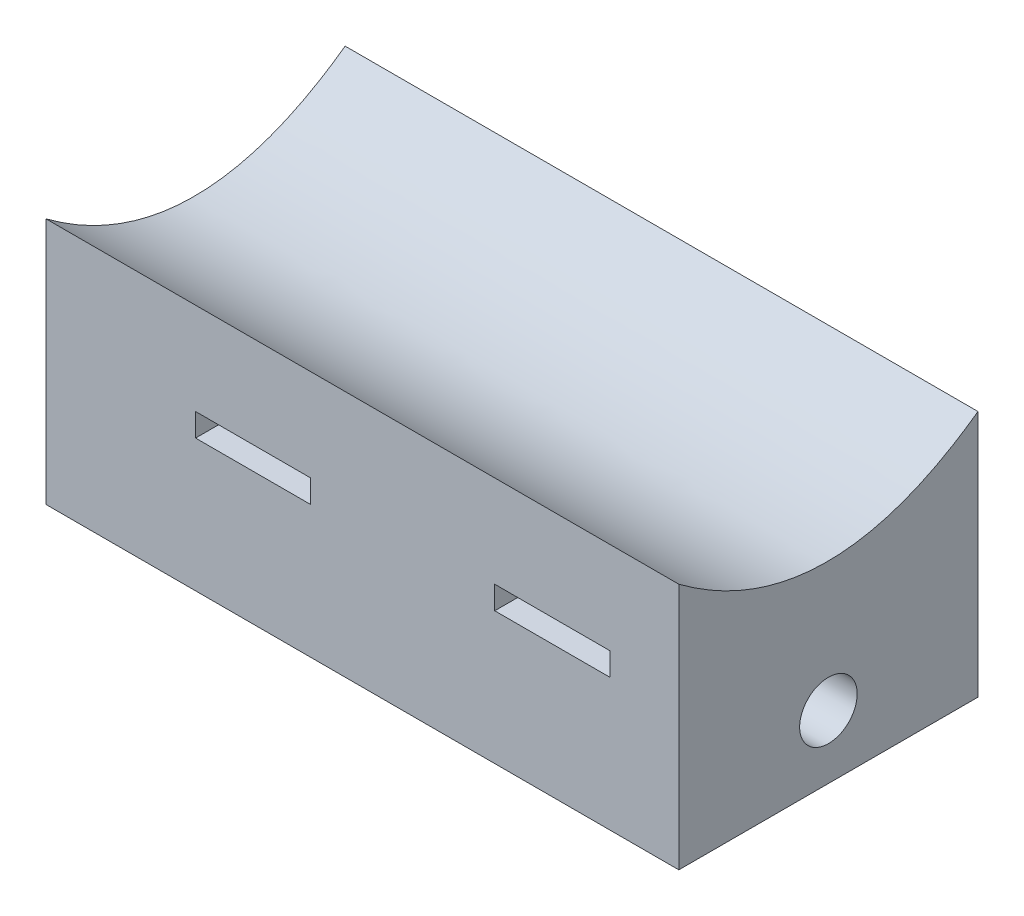
SolidWorks part; units mm, degrees
ref_plane "Plan de face" through (0, 0, 0) normal (0, 0, 1) x (1, 0, 0)
ref_plane "Plan de dessus" through (0, 0, 0) normal (0, 1, 0) x (1, 0, 0)
ref_plane "Plan de droite" through (0, 0, 0) normal (1, 0, 0) x (0, 0, -1)
sketch "Esquisse1" plane through (0, 0, 0) normal (0, 1, 0) x (1, 0, 0)
  line L1 (-24.8567, 8.6488) -> (30.1433, 8.6488)
  line L2 (-24.8567, 8.6488) -> (-24.8567, -17.3512)
  line L3 (-24.8567, -17.3512) -> (30.1433, -17.3512)
  line L4 (30.1433, 8.6488) -> (30.1433, -17.3512)
  dimension "D1" = 55
  dimension "D2" = 26
extrude "Boss.-Extru.1" add sketch "Esquisse1" along normal blind 25
sketch "Esquisse2" plane through (0, 0, 17.3512) normal (0, 0, 1) x (1, 0, 0)
  line L1 (30.1433, 25) -> (30.1433, 0) construction
  line L2 (14.1433, 17) -> (24.1433, 17)
  line L3 (14.1433, 17) -> (14.1433, 15)
  line L4 (14.1433, 15) -> (24.1433, 15)
  line L5 (24.1433, 17) -> (24.1433, 15)
  line L6 (-24.8567, 25) -> (30.1433, 25) construction
  line L7 (6.1433, 25) -> (6.1433, 0) construction
  line L8 (-24.8567, 0) -> (30.1433, 0) construction
  line L9 (-1.8567, 17) -> (-1.8567, 15)
  line L10 (-1.8567, 15) -> (-11.8567, 15)
  line L11 (-11.8567, 17) -> (-11.8567, 15)
  line L12 (-1.8567, 17) -> (-11.8567, 17)
  dimension "D1" = 10
  dimension "D2" = 2
  dimension "D3" = 6
  dimension "D4" = 8
  dimension "D5" = 24
extrude "Enlèv. mat.-Extru.1" cut sketch "Esquisse2" against normal up to next
sketch "Esquisse5" plane through (30.1433, 0, 0) normal (1, 0, 0) x (0, 0, -1)
  line L0 (8.6488, 25) -> (8.6488, 0) construction
  line L1 (-17.3512, 25) -> (8.6488, 25) construction
  line L2 (-17.3512, 25) -> (8.6488, 25)
  line L3 (-4.3512, 25) -> (-4.3512, 3.5) construction
  line L4 (-17.3512, 0) -> (8.6488, 0)
  line L5 (-17.3512, 0) -> (-17.3512, 3.5)
  line L6 (-17.3512, 3.5) -> (8.6488, 3.5)
  line L7 (8.6488, 0) -> (8.6488, 3.5)
  circle A0 centre (-4.3512, 9) radius 2.5
  spline S0 degree 2 poles (-17.3512, 25) (-4.5869, 15.5026) (8.6488, 25) knots 0 0 0 1 1 1
  point P18 (-4.3512, 9)
  dimension "D2" = 16
  dimension "D3" = 3.5
extrude "Enlèv. mat.-Extru.5" cut sketch "Esquisse5" against normal up to next
sketch "Esquisse9" plane through (0, 0, -8.6488) normal (0, 0, -1) x (-1, 0, 0)
  line L0 (-24.1433, 17) -> (-30.1433, 17) construction
  line L1 (-30.1433, 25) -> (-30.1433, 3.5) construction
sketch "Esquisse10" plane through (30.1433, 0, 0) normal (1, 0, 0) x (0, 0, -1)
  line L0 (8.6488, 17) -> (-17.3512, 17) construction
  line L1 (-17.3512, 25) -> (-17.3512, 3.5) construction
  line L2 (-4.3512, 17) -> (-4.3512, 20.2517) construction
  parabola Q0 (-17.3512, 25) -> (8.6488, 25) focus (-4.6897, 29.1431) apex (-4.9102, 20.2568) construction
